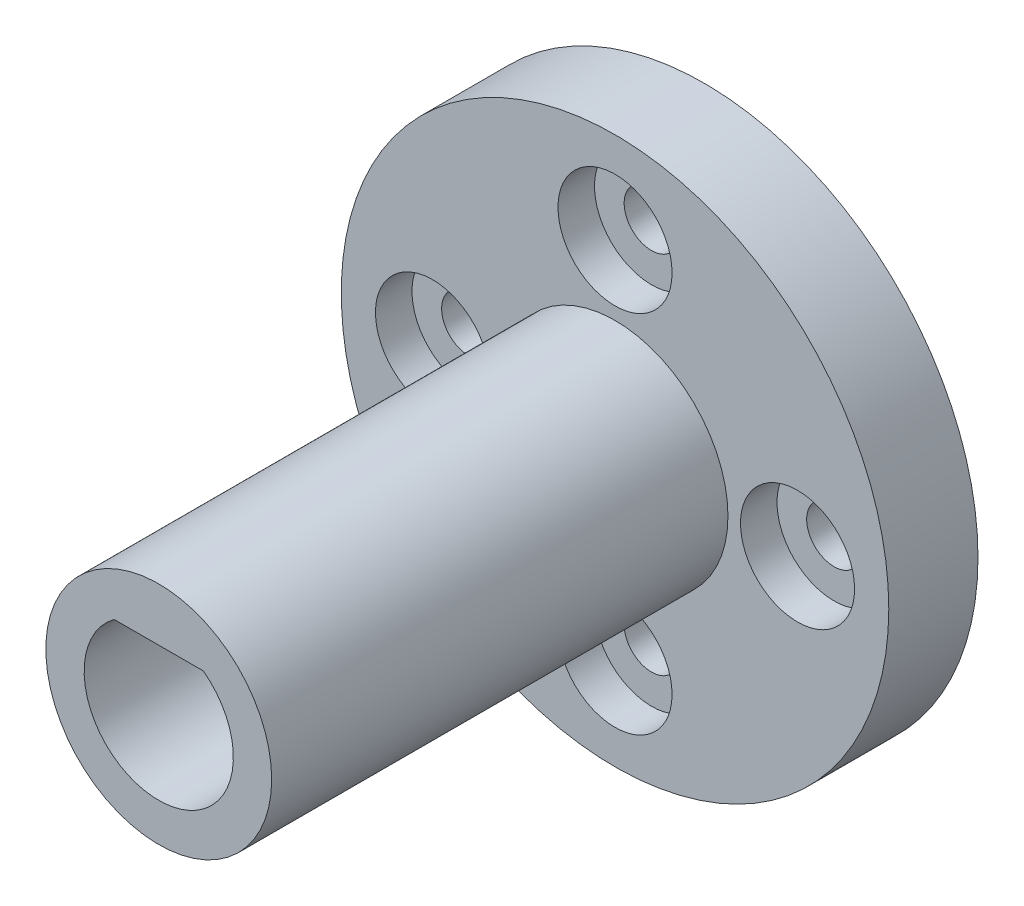
SolidWorks part; units mm, degrees
ref_plane "Plan de face" through (0, 0, 0) normal (0, 0, 1) x (1, 0, 0)
ref_plane "Plan de dessus" through (0, 0, 0) normal (0, 1, 0) x (1, 0, 0)
ref_plane "Plan de droite" through (0, 0, 0) normal (1, 0, 0) x (0, 0, -1)
sketch "Esquisse1" plane through (0, 0, 0) normal (0, 0, 1) x (1, 0, 0)
  circle A0 centre (0, 0) radius 12
  dimension "D1" = 24
extrude "Boss.-Extru.1" add sketch "Esquisse1" along normal blind 3.91
sketch "Esquisse6" plane through (0, 0, 0) normal (0, 0, -1) x (-1, 0, 0)
  circle A0 centre (0, 0) radius 4
  dimension "D1" = 8
extrude "Enlèv. mat.-Extru.2" cut sketch "Esquisse6" against normal blind 1.91
sketch "Esquisse7" plane through (0, 0, 3.91) normal (0, 0, 1) x (1, 0, 0)
  line L0 (1.9567, 2.62) -> (-1.9567, 2.62)
  line L1 (-5.4714, -3.27) -> (6.192, -3.27) construction
  arc A0 (-1.9567, 2.62) -> (1.9567, 2.62) centre (0, 0) ccw
  circle A1 centre (0, 0) radius 4.95
  dimension "D1" = 6.54
  dimension "D3" = 9.9
  dimension "D2" = 5.89
extrude "Boss.-Extru.2" add sketch "Esquisse7" along normal blind 20 contours A1 L1 A0 L0 | L1 A1
hole_wizard "Chambrage pour vis à tête ronde bombée M21" positions "Esquisse10" profile "Esquisse11" counterbore size "M2" standard "Ansi Metric" end condition through all
sketch "Esquisse10" plane through (0, 0, 3.91) normal (0, 0, 1) x (1, 0, 0)
  point P0 (0, 8)
  dimension "D1" = 8
sketch "Esquisse11" plane through (0, 8, 3.91) normal (1, 0, 0) x (0, -1, 0)
  line L0 (0, 0) -> (0, 3.91)
  line L1 (0, 3.91) -> (1.2, 3.91)
  line L3 (1.2, 3.91) -> (1.2, 1.6)
  line L4 (1.2, 1.6) -> (2.5, 1.6)
  line L5 (2.5, 1.6) -> (2.5, 0)
  line L7 (2.5, 0) -> (0, 0)
  line L11 (0, -6.35) -> (0, 107.95) construction
  dimension "Diamètre du perçage jusqu'au prochain" = 2.4
  dimension "Profondeur du perçage jusqu'au prochain" = 3.91
  dimension "Diamètre du chambrage" = 5
  dimension "Profondeur du chambrage" = 1.6
pattern_circular "Répétition circulaire2" count 4 every 90 about axis through (0, 0, 0) along (0, 0, 1) of "Chambrage pour vis à tête ronde bombée M21"
